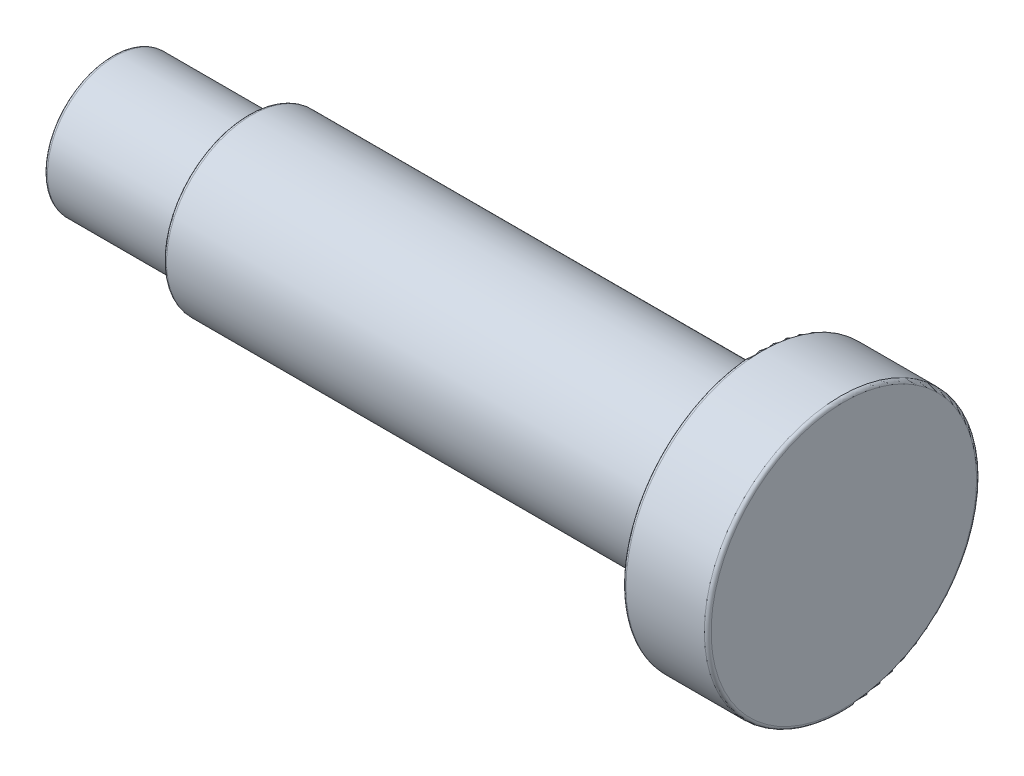
SolidWorks part; units mm, degrees
ref_plane "Front Plane" through (0, 0, 0) normal (0, 0, 1) x (1, 0, 0)
ref_plane "Top Plane" through (0, 0, 0) normal (0, 1, 0) x (1, 0, 0)
ref_plane "Right Plane" through (0, 0, 0) normal (1, 0, 0) x (0, 0, -1)
sketch "Sketch2" plane through (0, 0, 0) normal (1, 0, 0) x (0, 0, -1)
  circle A0 centre (0, 0) radius 63.5
  dimension "D1" = 127
extrude "Boss-Extrude1" add sketch "Sketch2" along normal mid plane 381
sketch "Sketch3" plane through (-190.5, 0, 0) normal (-1, 0, 0) x (0, 0, 1)
  circle A0 centre (0, 0) radius 50.8
  dimension "D1" = 101.6
extrude "Boss-Extrude2" add sketch "Sketch3" along normal blind 101.6
sketch "Sketch4" plane through (190.5, 0, 0) normal (1, 0, 0) x (0, 0, -1)
  circle A0 centre (0, 0) radius 101.6
  dimension "D1" = 203.2
extrude "Boss-Extrude3" add sketch "Sketch4" along normal blind 63.5
fillet "Fillet1" radius 2.54 2 edges at (190.5, 0, -101.6) (254, 0, -101.6)
fillet "Fillet2" radius 2.54 2 edges at (-190.5, 0, -63.5) (-292.1, 0, 50.8)
